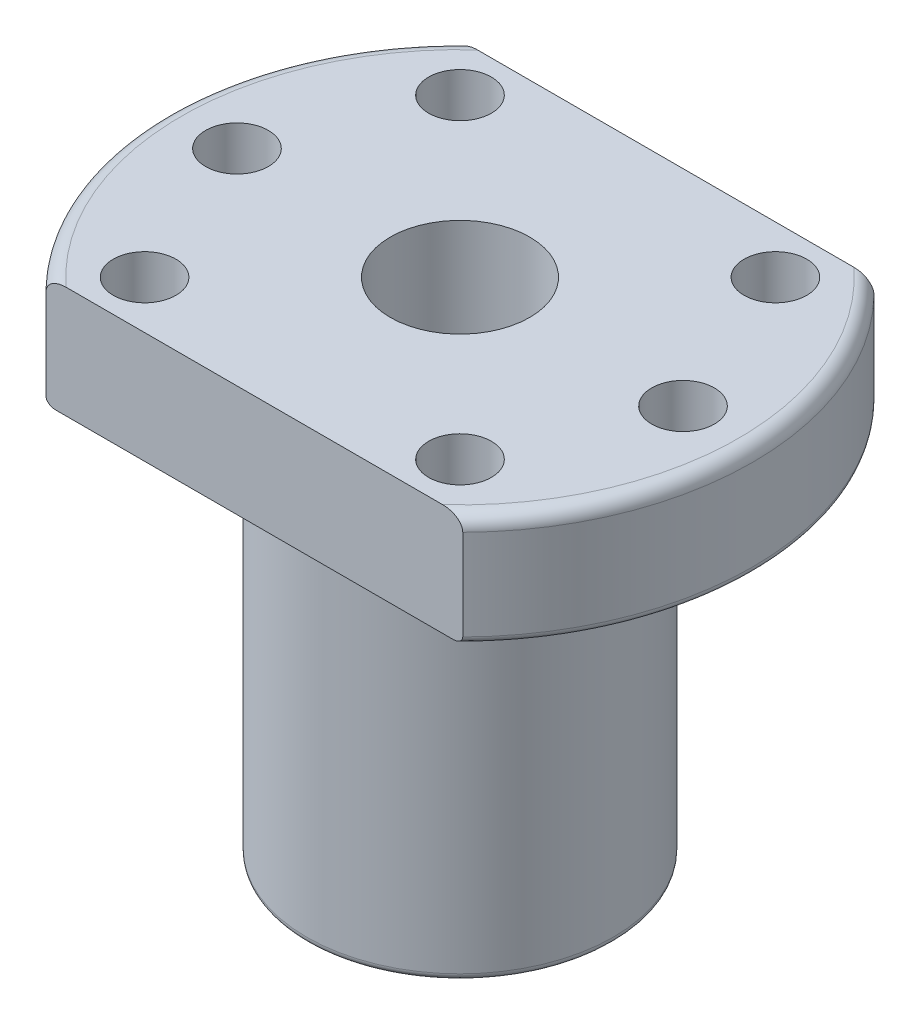
SolidWorks part; units mm, degrees
ref_plane "Front Plane" through (0, 0, 0) normal (0, 0, 1) x (1, 0, 0)
ref_plane "Top Plane" through (0, 0, 0) normal (0, 1, 0) x (1, 0, 0)
ref_plane "Right Plane" through (0, 0, 0) normal (1, 0, 0) x (0, 0, -1)
sketch "Sketch1" plane through (0, 0, 0) normal (0, 1, 0) x (1, 0, 0)
  line L0 (-14.9478, 14.75) -> (14.9478, 14.75)
  line L5 (-14.9478, -14.75) -> (14.9478, -14.75)
  line L6 (0, 14.75) -> (0, -14.75) construction
  arc A0 (-14.9478, 14.75) -> (-14.9478, -14.75) centre (0, 0) ccw
  arc A1 (14.9478, -14.75) -> (14.9478, 14.75) centre (0, 0) ccw
  circle A2 centre (0, 0) radius 5
  dimension "D1" = 21
  dimension "D3" = 10
  dimension "D2" = 29.5
extrude "Boss-Extrude1" add sketch "Sketch1" along normal blind 8
sketch "Sketch2" plane through (0, 0, 0) normal (0, -1, 0) x (1, 0, 0)
  circle A0 centre (0, 0) radius 11
  circle A1 centre (0, 0) radius 5 construction
  circle A2 centre (0, 0) radius 5
  dimension "D1" = 22
extrude "Boss-Extrude2" add sketch "Sketch2" along normal blind 28
sketch "Sketch3" plane through (0, 8, 0) normal (0, 1, 0) x (1, 0, 0)
  circle A0 centre (0, 0) radius 16 construction
  point P3 (16, 0)
  dimension "D1" = 32
hole_wizard "M4 Clearance Hole1" positions "Sketch4" profile "Sketch5" hole size "M4" standard "ISO" end condition through all
sketch "Sketch4" plane through (0, 8, 0) normal (0, 1, 0) x (1, 0, 0)
  point P0 (16, 0)
sketch "Sketch5" plane through (16, 8, 0) normal (1, 0, 0) x (0, 0, 1)
  line L0 (0, 0) -> (0, 36)
  line L1 (0, 36) -> (2.25, 36)
  line L2 (2.25, 36) -> (2.25, 0)
  line L5 (2.25, 0) -> (0, 0)
  line L11 (0, -6.35) -> (0, 107.95) construction
  dimension "Thru Hole Dia." = 4.5
  dimension "Thru Hole Depth" = 36
pattern_circular "CirPattern1" count 8 every 45 about axis through (0, 0, 0) along (0, 1, 0) skipping 2, 6 of "M4 Clearance Hole1"
fillet "Fillet1" radius 1 2 edges at (-21, 8, 0) (21, 8, 0)
fillet "Fillet2" radius 0.5 3 edges at (0, -28, -11) (21, 0, 0) (-21, 0, 0)
